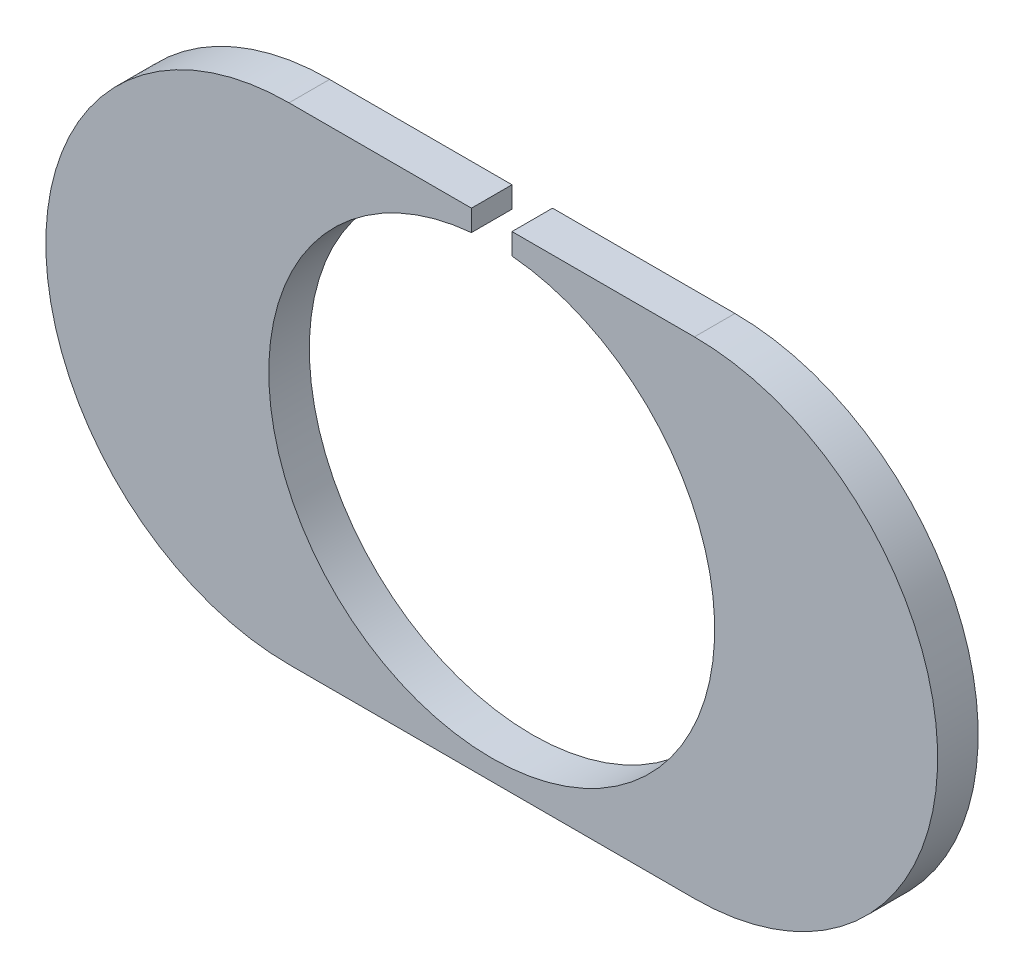
SolidWorks part; units mm, degrees
ref_plane "Front Plane" through (0, 0, 0) normal (0, 0, 1) x (1, 0, 0)
ref_plane "Top Plane" through (0, 0, 0) normal (0, 1, 0) x (1, 0, 0)
ref_plane "Right Plane" through (0, 0, 0) normal (1, 0, 0) x (0, 0, -1)
sketch "Sketch2" plane through (0, 0, 0) normal (0, 0, 1) x (1, 0, 0)
  line L0 (-50, 0) -> (50, 0) construction
  line L1 (-50, 60) -> (50, 60)
  line L2 (-50, -60) -> (50, -60)
  arc A0 (-50, 60) -> (-50, -60) centre (-50, 0) ccw
  arc A1 (50, -60) -> (50, 60) centre (50, 0) ccw
  circle A2 centre (0, 0) radius 55
  point P3 (0, 0)
  dimension "D2" = 110
  dimension "D3" = 60
  dimension "D1" = 100
extrude "Boss-Extrude1" add sketch "Sketch2" along normal blind 10
sketch "Sketch4" plane through (0, 0, 10) normal (0, 0, 1) x (1, 0, 0)
  line L0 (50, 60) -> (-50, 60) construction
  line L1 (-5, 54.7723) -> (5, 54.7723)
  line L2 (-5, 54.7723) -> (-5, 60)
  line L3 (-5, 60) -> (5, 60)
  line L4 (5, 54.7723) -> (5, 60)
  line L5 (0, 54.7723) -> (0, 0) construction
  circle A0 centre (0, 0) radius 55 construction
  dimension "D1" = 10
extrude "Cut-Extrude1" cut sketch "Sketch4" against normal up to next
